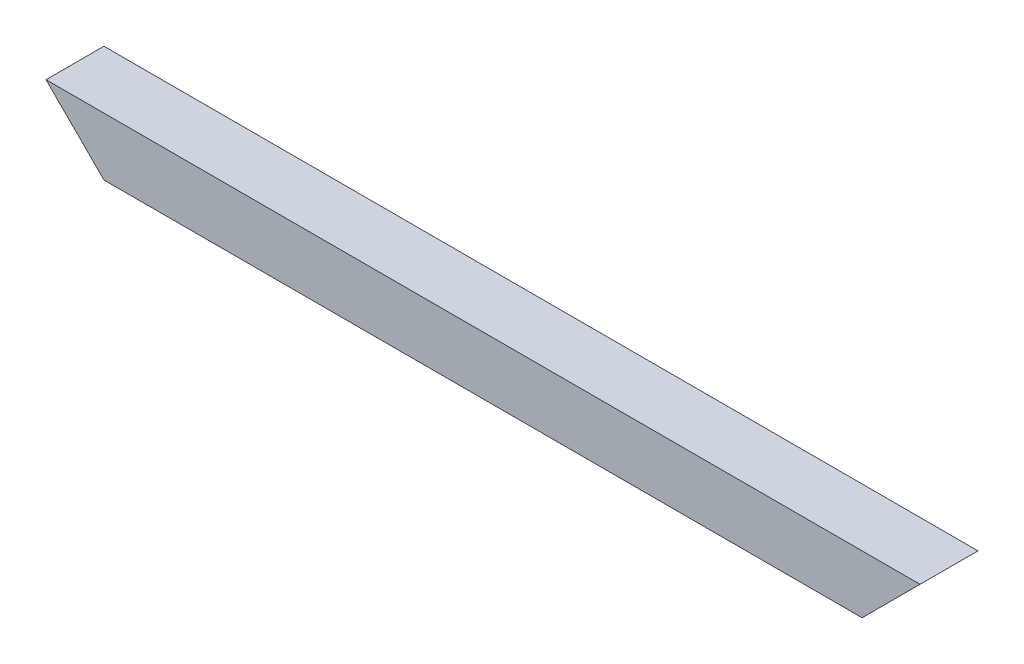
SolidWorks part; units mm, degrees
ref_plane "Front Plane" through (0, 0, 0) normal (0, 0, 1) x (1, 0, 0)
ref_plane "Top Plane" through (0, 0, 0) normal (0, 1, 0) x (1, 0, 0)
ref_plane "Right Plane" through (0, 0, 0) normal (1, 0, 0) x (0, 0, -1)
sketch "Sketch1" plane through (0, 0, 0) normal (1, 0, 0) x (0, 0, -1)
  line L1 (0, 0) -> (38.1, 0)
  line L2 (0, 0) -> (0, -38.1)
  line L3 (0, -38.1) -> (38.1, -38.1)
  line L4 (38.1, 0) -> (38.1, -38.1)
  dimension "D1" = 38.1
  dimension "D2" = 38.1
extrude "Boss-Extrude1" add sketch "Sketch1" along normal blind 574.7364
sketch "Sketch2" plane through (0, 0, 0) normal (0, 0, 1) x (1, 0, 0)
  line L0 (0, -38.1) -> (38.1, -38.1)
  line L1 (574.7364, -38.1) -> (0, -38.1) construction
  line L2 (38.1, -38.1) -> (0, 0)
  dimension "D1" = 38.1
extrude "Cut-Extrude1" cut sketch "Sketch2" against normal through all and the other way through all
sketch "Sketch3" plane through (0, 0, 0) normal (0, 0, 1) x (1, 0, 0)
  line L0 (574.7364, -38.1) -> (536.6364, -38.1)
  line L1 (574.7364, -38.1) -> (38.1, -38.1) construction
  line L2 (536.6364, -38.1) -> (574.7364, 0)
  dimension "D1" = 38.1
extrude "Cut-Extrude2" cut sketch "Sketch3" against normal through all and the other way through all flip side to cut
